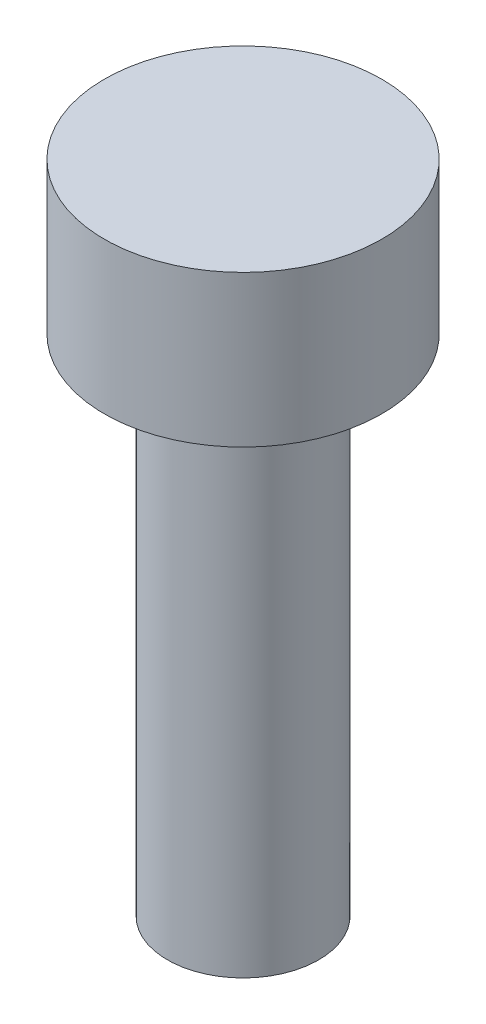
SolidWorks part; units mm, degrees
ref_plane "Front" through (0, 0, 0) normal (0, 0, 1) x (1, 0, 0)
ref_plane "Top" through (0, 0, 0) normal (0, 1, 0) x (1, 0, 0)
ref_plane "Right" through (0, 0, 0) normal (1, 0, 0) x (0, 0, -1)
sketch "Эскиз1" plane through (0, 0, 0) normal (0, 0, 1) x (1, 0, 0)
  line L0 (0, 13) -> (2.75, 13)
  line L1 (2.75, 13) -> (2.75, 10)
  line L2 (2.75, 10) -> (1.5, 10)
  line L3 (1.5, 10) -> (1.5, 0)
  line L4 (1.5, 0) -> (0, 0)
  line L5 (0, 0) -> (0, 13)
  dimension "D1" = 1.5
  dimension "D2" = 10
  dimension "D3" = 3
  dimension "D4" = 2.75
revolve "Повернуть1" add sketch "Эскиз1" angle 360 about L5
